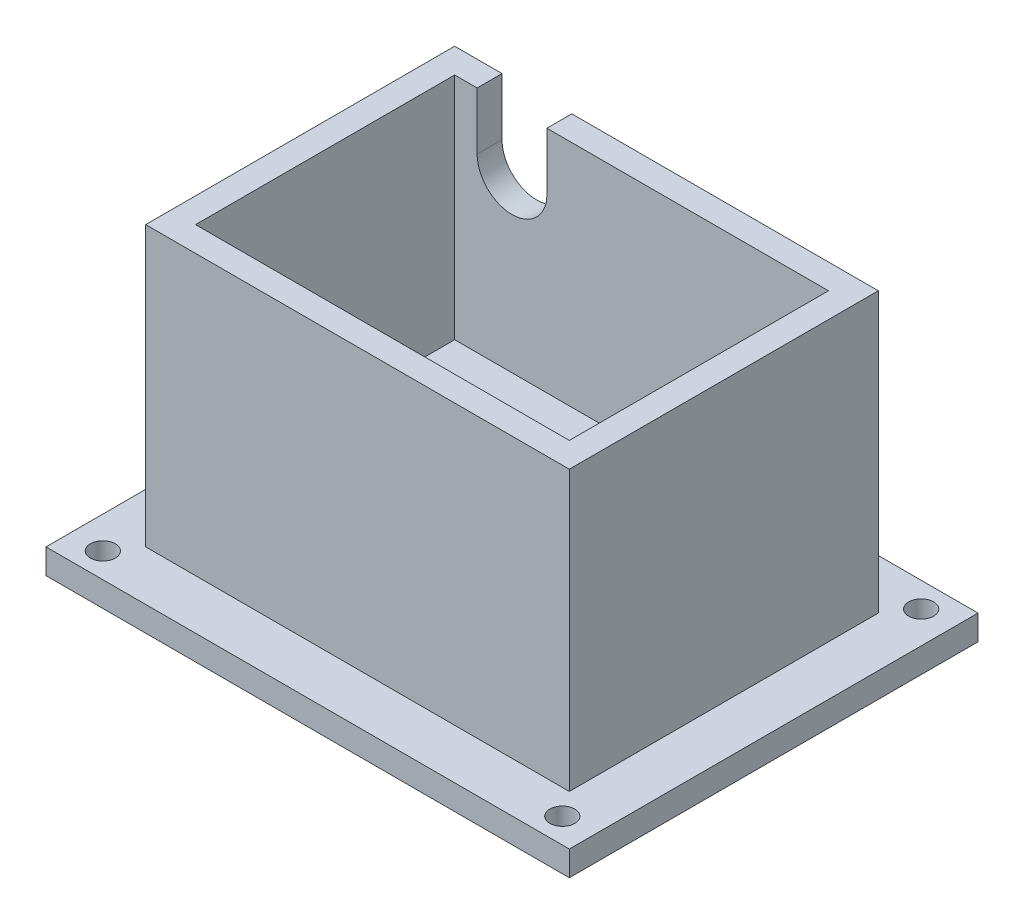
SolidWorks part; units mm, degrees
ref_plane "Front Plane" through (0, 0, 0) normal (0, 0, 1) x (1, 0, 0)
ref_plane "Top Plane" through (0, 0, 0) normal (0, 1, 0) x (1, 0, 0)
ref_plane "Right Plane" through (0, 0, 0) normal (1, 0, 0) x (0, 0, -1)
sketch "Sketch1" plane through (0, 0, 0) normal (0, 1, 0) x (1, 0, 0)
  line L1 (0, 0) -> (150, 0)
  line L2 (0, 0) -> (0, 104)
  line L3 (0, 104) -> (150, 104)
  line L4 (150, 0) -> (150, 104)
  dimension "D1" = 150
  dimension "D2" = 104
extrude "Boss-Extrude1" add sketch "Sketch1" along normal blind 30
sketch "Sketch2" plane through (0, 0, 0) normal (0, 1, 0) x (1, 0, 0)
  line L0 (75, 104) -> (75, 0) construction
  line L1 (150, 104) -> (0, 104) construction
  line L2 (0, 0) -> (150, 0) construction
  line L3 (0, 52) -> (150, 52) construction
  line L4 (0, 104) -> (0, 0) construction
  line L5 (150, 0) -> (150, 104) construction
  line L7 (-10, -10) -> (160, -10)
  line L8 (-10, -10) -> (-10, 114)
  line L9 (-10, 114) -> (160, 114)
  line L10 (160, -10) -> (160, 114)
  line L11 (-10, -10) -> (160, 114) construction
  line L12 (-10, 114) -> (160, -10) construction
  line L16 (0, 104) -> (0, 0)
  line L17 (0, 0) -> (150, 0)
  line L18 (150, 0) -> (150, 104)
  line L19 (150, 104) -> (0, 104)
  line L20 (0, 104) -> (0, 0)
  line L21 (0, 0) -> (150, 0)
  line L22 (150, 0) -> (150, 104)
  line L23 (150, 104) -> (0, 104)
  point P12 (75, 52)
  dimension "D1" = 10
  dimension "D2" = 10
  dimension "D3" = 0
extrude "Boss-Extrude2" add sketch "Sketch2" along normal blind 122
sketch "Sketch3" plane through (0, 0, 0) normal (0, -1, 0) x (1, 0, 0)
  line L0 (160, -52) -> (-10, -52) construction
  line L1 (160, 10) -> (160, -114) construction
  line L2 (-10, -114) -> (-10, 10) construction
  line L3 (-10, 10) -> (160, 10) construction
  point P0 (75, -52)
  point P1 (0, 0)
  dimension "D1" = 85
  dimension "D2" = 62
sketch "Sketch5" plane through (0, 0, -114) normal (0, 0, -1) x (-1, 0, 0)
  line L0 (-37, 122) -> (-37, 99)
  line L1 (-160, 122) -> (10, 122) construction
  line L2 (-9, 99) -> (-9, 122)
  line L3 (-9, 122) -> (-37, 122)
  line L4 (10, 122) -> (10, 0) construction
  arc A0 (-37, 99) -> (-9, 99) centre (-23, 99) ccw
  point P6 (0, 0)
  dimension "D2" = 14
  dimension "D1" = 23
  dimension "D3" = 33
extrude "Cut-Extrude2" cut sketch "Sketch5" against normal up to surface (10 mm away) up to face at (75, 76, -104)
sketch "Sketch6" plane through (0, 0, 0) normal (0, 1, 0) x (1, 0, 0)
  line L0 (160, 114) -> (37, 114) construction
  line L1 (-30, -30) -> (180, -30)
  line L2 (-30, -30) -> (-30, 134)
  line L3 (-30, 134) -> (180, 134)
  line L4 (180, -30) -> (180, 134)
  line L5 (-30, -30) -> (180, 134) construction
  line L6 (-30, 134) -> (180, -30) construction
  line L7 (160, -10) -> (160, 114) construction
  circle A0 centre (-17.1951, -20) radius 5
  circle A1 centre (167.1951, -20) radius 5
  circle A2 centre (167.1951, 124) radius 5
  circle A3 centre (-17.1951, 124) radius 5
  point P0 (75, 52)
  point P18 (0, 0)
  point P19 (0, 0)
  point P20 (0, 0)
  point P21 (0, 0)
  dimension "D3" = 10
  dimension "D1" = 20
  dimension "D2" = 20
  dimension "D4" = 10
extrude "Boss-Extrude3" add sketch "Sketch6" along normal blind 10
